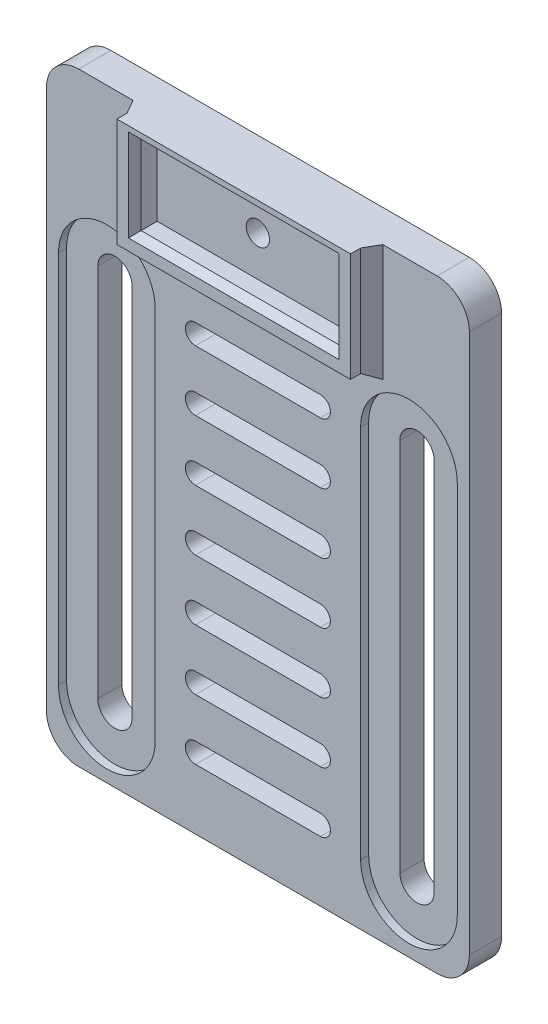
SolidWorks part; units mm, degrees
other "Marca1"
sketch "Croquis5" plane through (0, 0, 14) normal (0, 0, 1) x (1, 0, 0)
ref_plane "Alzado" through (0, 0, 0) normal (0, 0, 1) x (1, 0, 0)
ref_plane "Planta" through (0, 0, 0) normal (0, 1, 0) x (1, 0, 0)
ref_plane "Vista lateral" through (0, 0, 0) normal (1, 0, 0) x (0, 0, -1)
sketch "Croquis1" plane through (0, 0, 0) normal (0, 0, 1) x (1, 0, 0)
  line L1 (0, 0) -> (105, 0)
  line L2 (0, 0) -> (0, 150)
  line L3 (0, 150) -> (105, 150)
  line L4 (105, 0) -> (105, 150)
  dimension "D1" = 150
  dimension "D2" = 105
extrude "Saliente-Extruir1" add sketch "Croquis1" along normal blind 8
sketch "Croquis2" plane through (0, 0, 8) normal (0, 0, 1) x (1, 0, 0)
  line L0 (52.5, 150) -> (52.5, 0) construction
  line L1 (105, 150) -> (0, 150) construction
  line L2 (0, 0) -> (105, 0) construction
  line L3 (30, 150) -> (30, 0) construction
  line L4 (80, 150) -> (80, 0) construction
  line L5 (0, 150) -> (0, 0) construction
  line L6 (105, 0) -> (105, 150) construction
  line L7 (30, 150) -> (0, 150) construction
  line L8 (15, 150) -> (15, 0) construction
  line L9 (80, 150) -> (105, 150) construction
  line L10 (92.5, 150) -> (92.5, 0) construction
  line L11 (0, 123) -> (105, 123) construction
  line L12 (15, 108) -> (15, 15) construction
  line L13 (19.25, 108) -> (19.25, 15)
  line L14 (10.75, 108) -> (10.75, 15)
  line L15 (90, 108) -> (90, 15) construction
  line L16 (85.75, 108) -> (85.75, 15)
  line L17 (94.25, 108) -> (94.25, 15)
  line L18 (0, 147) -> (105, 147) construction
  line L19 (0, 127) -> (105, 127) construction
  line L20 (52.5, 147) -> (52.5, 127)
  arc A0 (19.25, 108) -> (10.75, 108) centre (15, 108) ccw
  arc A1 (10.75, 15) -> (19.25, 15) centre (15, 15) ccw
  arc A2 (85.75, 108) -> (94.25, 108) centre (90, 108) cw
  arc A3 (94.25, 15) -> (85.75, 15) centre (90, 15) cw
  circle A4 centre (52.5, 137) radius 2.9
  point P26 (15, 61.5)
  point P33 (90, 61.5)
  dimension "D5" = 15
  dimension "D6" = 15
  dimension "D1" = 30
  dimension "D2" = 25
  dimension "D3" = 4
  dimension "D4" = 8.5
  dimension "D7" = 3
  dimension "D8" = 20
extrude "Cortar-Extruir4" cut sketch "Croquis2" against normal up to surface (8 mm away) contours L13 A1 L14 A0 | L17 A3 L16 A2 | A4 up to face at (52.5, 75, 0)
sketch "Croquis3" plane through (0, 0, 8) normal (0, 0, 1) x (1, 0, 0)
  line L0 (105, 150) -> (0, 150) construction
  line L1 (105, 0) -> (105, 150) construction
  line L3 (25, 150) -> (0, 150) construction
  line L5 (77.5, 150) -> (104.1126, 150) construction
  line L7 (2.5, 123) -> (102.5, 123) construction
  line L14 (0, 147) -> (105, 147) construction
  line L15 (2.5, 127) -> (102.5, 127) construction
  line L16 (52.5, 147) -> (52.5, 127)
  line L17 (23.5, 150) -> (23.5, 123)
  line L18 (23.5, 123) -> (81.5, 123)
  line L19 (81.5, 123) -> (81.5, 150)
  line L20 (81.5, 150) -> (23.5, 150)
  line L22 (27.5, 147.5) -> (77.5, 147.5)
  line L23 (27.5, 147.5) -> (27.5, 127)
  line L24 (27.5, 127) -> (77.5, 127)
  line L25 (77.5, 147.5) -> (77.5, 127)
  circle A4 centre (52.5, 137) radius 2.9
  line M26 (105, 150) -> (0, 150)
  dimension "D5" = 25
  dimension "D1" = 4
  dimension "D2" = 4
  dimension "D3" = 20.5
  dimension "D4" = 23.5
extrude "Saliente-Extruir2" add sketch "Croquis3" along normal blind 6 contours L18 L19 L17 L22 L25 L24 L23 M26
fillet "Redondeo1" radius 8 1 edges at (0, 150, 4)
fillet "Redondeo2" radius 8 1 edges at (105, 150, 4)
fillet "Redondeo3" radius 8 1 edges at (0, 0, 4)
fillet "Redondeo4" radius 8 1 edges at (105, 0, 4)
sketch "Croquis4" plane through (0, 0, 8) normal (0, 0, 1) x (1, 0, 0)
  line L0 (85.75, 108) -> (85.75, 15) construction
  line L1 (94.25, 108) -> (94.25, 15) construction
  line L2 (85.75, 108) -> (85.75, 15)
  line L3 (94.25, 108) -> (94.25, 15)
  line L4 (10.75, 108) -> (10.75, 15) construction
  line L5 (19.25, 108) -> (19.25, 15) construction
  line L6 (10.75, 108) -> (10.75, 15)
  line L7 (19.25, 108) -> (19.25, 15)
  line L8 (15, 108) -> (15, 15) construction
  line L9 (27, 108) -> (27, 15)
  line L10 (3, 108) -> (3, 15)
  line L11 (52.5, 147.5) -> (52.5, 0) construction
  line L14 (27.5, 147.5) -> (77.5, 147.5) construction
  line L15 (8, 0) -> (97, 0) construction
  line L16 (90, 108) -> (90, 15) construction
  line L17 (78, 108) -> (78, 15)
  line L18 (102, 108) -> (102, 15)
  arc A0 (85.75, 15) -> (94.25, 15) centre (90, 15) ccw construction
  arc A1 (94.25, 108) -> (85.75, 108) centre (90, 108) ccw construction
  arc A2 (85.75, 15) -> (94.25, 15) centre (90, 15) ccw
  arc A3 (94.25, 108) -> (85.75, 108) centre (90, 108) ccw
  arc A4 (10.75, 15) -> (19.25, 15) centre (15, 15) ccw construction
  arc A5 (19.25, 108) -> (10.75, 108) centre (15, 108) ccw construction
  arc A6 (10.75, 15) -> (19.25, 15) centre (15, 15) ccw
  arc A7 (19.25, 108) -> (10.75, 108) centre (15, 108) ccw
  arc A8 (27, 108) -> (3, 108) centre (15, 108) ccw
  arc A9 (3, 15) -> (27, 15) centre (15, 15) ccw
  arc A12 (78, 108) -> (102, 108) centre (90, 108) cw
  arc A13 (102, 15) -> (78, 15) centre (90, 15) cw
  point P12 (15, 61.5)
  point P25 (90, 61.5)
  dimension "D1" = 24
extrude "Cortar-Extruir5" cut sketch "Croquis4" against normal blind 2
chamfer "Chaflán1" distance 2 angle 30 4 edges at (52.5, 127, 14) (77.5, 137.25, 14) (27.5, 137.25, 14) (52.5, 147.5, 14)
chamfer "Chaflán2" distance 2 angle 60 3 edges at (23.5, 136.5, 8) (52.5, 123, 8) (81.5, 136.5, 8)
sketch "Croquis6" plane through (0, 0, 8) normal (0, 0, 1) x (1, 0, 0)
  line L0 (37, 17.5) -> (68, 17.5) construction
  line L1 (37, 20) -> (68, 20)
  line L2 (37, 15) -> (68, 15)
  line L3 (78, 108) -> (78, 15) construction
  line L4 (27, 15) -> (27, 108) construction
  line L5 (37, 30) -> (68, 30)
  line L6 (37, 35) -> (68, 35)
  line L7 (37, 32.5) -> (68, 32.5) construction
  line L8 (37, 45) -> (68, 45)
  line L9 (37, 50) -> (68, 50)
  line L10 (37, 47.5) -> (68, 47.5) construction
  line L11 (37, 60) -> (68, 60)
  line L12 (37, 65) -> (68, 65)
  line L13 (37, 62.5) -> (68, 62.5) construction
  line L14 (37, 75) -> (68, 75)
  line L15 (37, 80) -> (68, 80)
  line L16 (37, 77.5) -> (68, 77.5) construction
  line L17 (37, 90) -> (68, 90)
  line L18 (37, 95) -> (68, 95)
  line L19 (37, 92.5) -> (68, 92.5) construction
  line L20 (37, 105) -> (68, 105)
  line L21 (37, 110) -> (68, 110)
  line L22 (37, 107.5) -> (68, 107.5) construction
  arc A0 (37, 20) -> (37, 15) centre (37, 17.5) ccw
  arc A1 (68, 15) -> (68, 20) centre (68, 17.5) ccw
  arc A2 (10.75, 15) -> (19.25, 15) centre (15, 15) ccw construction
  arc A3 (37, 35) -> (37, 30) centre (37, 32.5) ccw
  arc A4 (68, 30) -> (68, 35) centre (68, 32.5) ccw
  arc A5 (37, 50) -> (37, 45) centre (37, 47.5) ccw
  arc A6 (68, 45) -> (68, 50) centre (68, 47.5) ccw
  arc A7 (37, 65) -> (37, 60) centre (37, 62.5) ccw
  arc A8 (68, 60) -> (68, 65) centre (68, 62.5) ccw
  arc A9 (37, 80) -> (37, 75) centre (37, 77.5) ccw
  arc A10 (68, 75) -> (68, 80) centre (68, 77.5) ccw
  arc A11 (37, 95) -> (37, 90) centre (37, 92.5) ccw
  arc A12 (68, 90) -> (68, 95) centre (68, 92.5) ccw
  arc A13 (37, 110) -> (37, 105) centre (37, 107.5) ccw
  arc A14 (68, 105) -> (68, 110) centre (68, 107.5) ccw
  point P2 (52.5, 17.5)
  point P18 (52.5, 32.5)
  point P25 (52.5, 47.5)
  point P32 (52.5, 62.5)
  point P39 (52.5, 77.5)
  point P46 (52.5, 92.5)
  point P53 (52.5, 107.5)
  dimension "D1" = 10
  dimension "D2" = 10
  dimension "D4" = 0
  dimension "D3" = 5
  dimension "D6" = 10
  dimension "D5" = 7
extrude "Cortar-Extruir6" cut sketch "Croquis6" against normal up to surface (8 mm away) up to face at (15, 61.5, 0)
